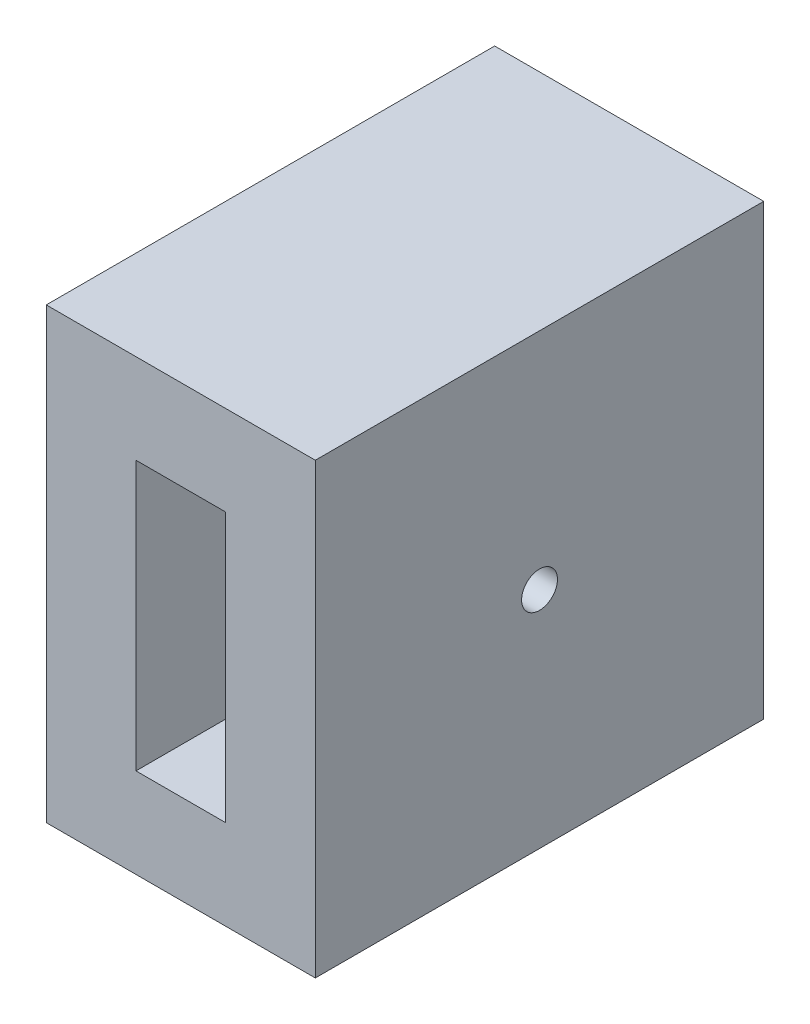
SolidWorks part; units mm, degrees
ref_plane "Front Plane" through (0, 0, 0) normal (0, 0, 1) x (1, 0, 0)
ref_plane "Top Plane" through (0, 0, 0) normal (0, 1, 0) x (1, 0, 0)
ref_plane "Right Plane" through (0, 0, 0) normal (1, 0, 0) x (0, 0, -1)
sketch "Sketch1" plane through (0, 0, 0) normal (0, 0, 1) x (1, 0, 0)
  line L0 (-15, 25) -> (15, 25)
  line L1 (-5, 15) -> (5, 15)
  line L2 (-5, 15) -> (-5, -15)
  line L3 (-5, -15) -> (5, -15)
  line L4 (5, 15) -> (5, -15)
  line L5 (-5, 15) -> (5, -15) construction
  line L6 (-5, -15) -> (5, 15) construction
  line L7 (15, 25) -> (15, -25)
  line L8 (-15, -25) -> (15, -25)
  line L9 (-15, 25) -> (-15, -25)
  point P0 (0, 0)
  dimension "D1" = 30
  dimension "D2" = 10
  dimension "D3" = 10
extrude "Boss-Extrude2" add sketch "Sketch1" along normal blind 50
sketch "Sketch2" plane through (15, 0, 0) normal (1, 0, 0) x (0, 0, -1)
  circle A0 centre (-25, 0) radius 2
  dimension "D1" = 4
extrude "Cut-Extrude1" cut sketch "Sketch2" against normal blind 10
